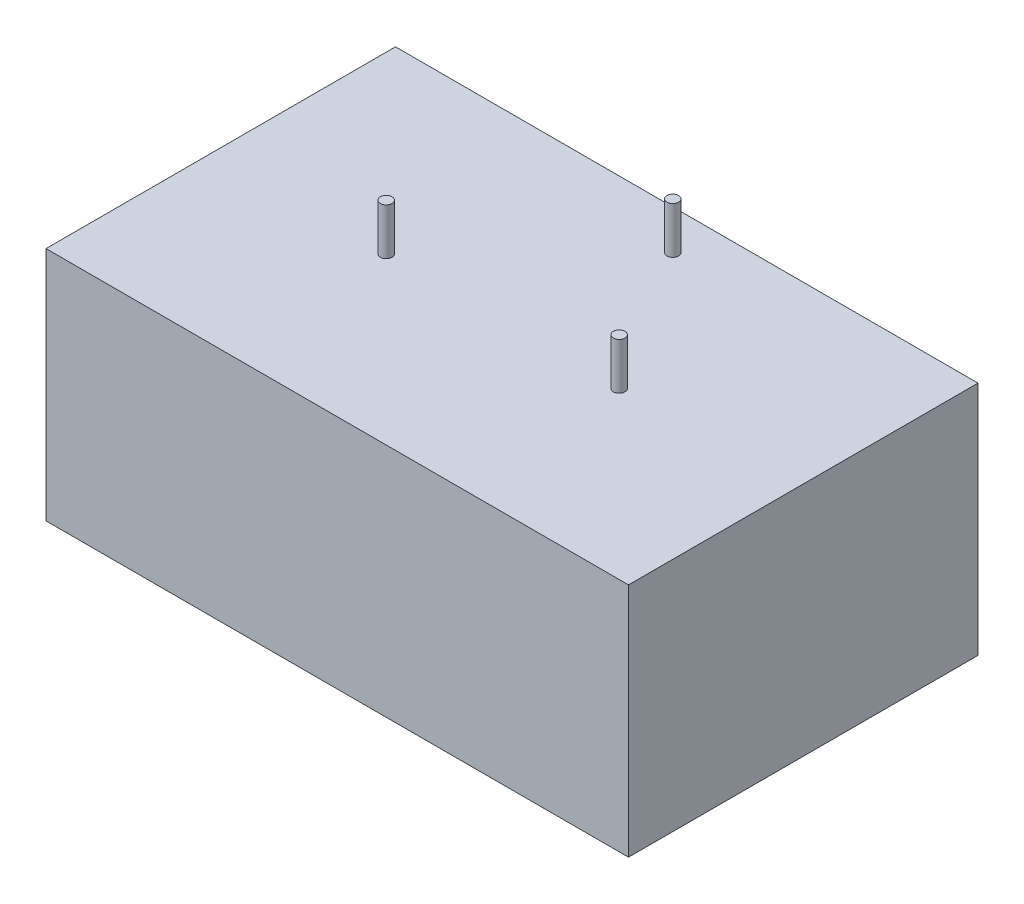
SolidWorks part; units mm, degrees
ref_plane "前视基准面" through (0, 0, 0) normal (0, 0, 1) x (1, 0, 0)
ref_plane "上视基准面" through (0, 0, 0) normal (0, 1, 0) x (1, 0, 0)
ref_plane "右视基准面" through (0, 0, 0) normal (1, 0, 0) x (0, 0, -1)
other "Configuration Table"
sketch "草图2" plane through (0, 0, 0) normal (0, 1, 0) x (1, 0, 0)
  line L1 (-125, 75) -> (125, 75)
  line L2 (-125, 75) -> (-125, -75)
  line L3 (-125, -75) -> (125, -75)
  line L4 (125, 75) -> (125, -75)
  line L5 (-125, 75) -> (125, -75) construction
  line L6 (-125, -75) -> (125, 75) construction
  point P0 (0, 0)
  dimension "D1" = 250
  dimension "D2" = 150
extrude "凸台-拉伸1" add sketch "草图2" along normal blind 80.07
sketch "草图6" plane through (0, 0, -75) normal (0, 0, -1) x (-1, 0, 0)
  line L0 (-125, 40.035) -> (125, 40.035) construction
  line L1 (-125, 80.07) -> (-125, 0) construction
  line L2 (125, 80.07) -> (125, 0) construction
  line L3 (0, 80.07) -> (0, 0) construction
  line L4 (-125, 80.07) -> (125, 80.07) construction
  circle A0 centre (-22.5, 40.035) radius 7.5
  circle A1 centre (22.5, 40.035) radius 7.5
  dimension "D3" = 15
  dimension "D1" = 45
  dimension "D2" = 45
extrude "切除-拉伸1" cut sketch "草图6" against normal blind 20
sketch "草图7" plane through (0, 80.07, 0) normal (0, 1, 0) x (1, 0, 0)
  line L4 (125, -75) -> (125, 75)
  line L5 (125, 75) -> (-125, 75)
  line L6 (-125, 75) -> (-125, -75)
  line L7 (-125, -75) -> (125, -75)
  line L8 (125, -75) -> (125, 75)
  line L9 (125, 75) -> (-125, 75)
  line L10 (-125, 75) -> (-125, -75)
  line L11 (-125, -75) -> (125, -75)
  dimension "D2" = 250
  dimension "D1" = 0
extrude "凸台-拉伸2" add sketch "草图7" along normal blind 21.15
sketch "草图13" plane through (0, 101.22, 0) normal (0, 1, 0) x (1, 0, 0)
  line L0 (0, 0) -> (0, 218.2821) construction
  line L1 (203.0283, 0) -> (-203.0283, 0) construction
  line L2 (125, 43.2617) -> (-125, 75.5825) construction
  line L3 (125, -75) -> (125, 75) construction
  line L4 (-125, 75) -> (-125, -75) construction
  circle A0 centre (11, 58) radius 2.5
  point P6 (0, 0)
  point P14 (0, 0)
  dimension "D1" = 5
extrude "凸台-拉伸4" add sketch "草图13" along normal blind 20
sketch "草图15" plane through (0, 101.22, 0) normal (0, 1, 0) x (1, 0, 0)
  line L1 (0, -117.3) -> (0, 117.3) construction
  circle A0 centre (0, 125) radius 7.7 construction
  circle A1 centre (50, -4) radius 2.5
  circle A2 centre (-50, -4) radius 2.5
  point P10 (0, 0)
  dimension "D1" = 5
extrude "凸台-拉伸5" add sketch "草图15" along normal blind 20
